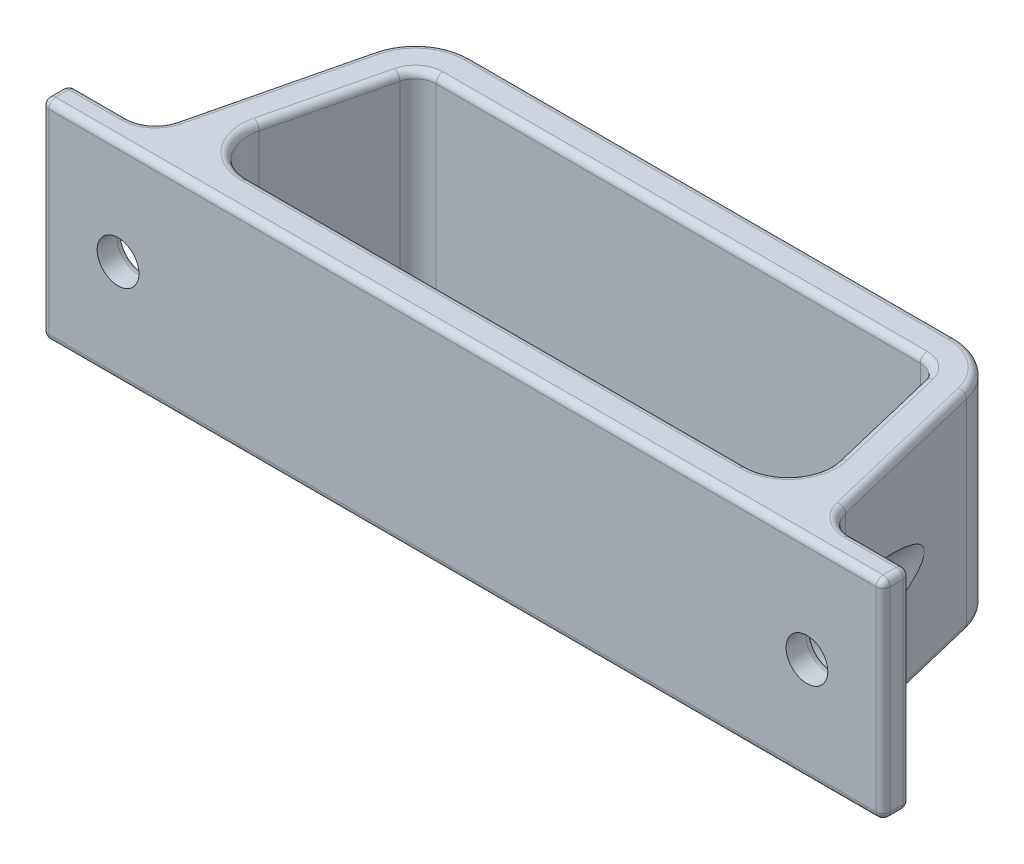
SolidWorks part; units mm, degrees
ref_plane "Front Plane" through (0, 0, 0) normal (0, 0, 1) x (1, 0, 0)
ref_plane "Top Plane" through (0, 0, 0) normal (0, 1, 0) x (1, 0, 0)
ref_plane "Right Plane" through (0, 0, 0) normal (1, 0, 0) x (0, 0, -1)
sketch "Sketch1" plane through (0, 0, 0) normal (0, 1, 0) x (1, 0, 0)
  line L15 (-28.2557, 3.4685) -> (-25.4887, 14.9381)
  line L16 (-30.1999, 1.9375) -> (-33.9268, 1.9375)
  line L17 (-34.4268, 1.4375) -> (-34.4268, 0.5)
  line L30 (-25.0241, 6.2036) -> (-23.0584, 14.3518)
  line L31 (25.8254, 2.8822) -> (23.0584, 14.3518) construction
  line L32 (-25.9357, 2.5) -> (25.9357, 2.5) construction
  line L33 (-25.8254, 2.8822) -> (-23.0584, 14.3518) construction
  line L35 (32.75, 1.4375) -> (32.75, 0.5) construction
  line L36 (30.1999, 1.9375) -> (32.25, 1.9375) construction
  line L37 (28.2557, 3.4685) -> (25.4887, 14.9381) construction
  line L38 (-21.6002, 18) -> (21.6002, 18) construction
  line L39 (-33.9268, 0) -> (32.25, 0) construction
  line L40 (-21.6002, 15.5) -> (21.6002, 15.5) construction
  line L41 (25.9357, 2.5) -> (25.9357, 2.5) construction
  line L42 (25.9357, 2.5) -> (25.9357, 2.5) construction
  line L48 (-25.9357, 2.5) -> (-25.9357, 2.5) construction
  line L49 (-25.9357, 2.5) -> (-25.9357, 2.5) construction
  line L50 (-4.205, 18) -> (-4.205, -5.5278) construction
  line L57 (16.6141, 6.2036) -> (14.6483, 14.3518)
  line L58 (26.0167, 1.4375) -> (26.0167, 0.5)
  line L59 (21.7898, 1.9375) -> (25.5167, 1.9375)
  line L60 (19.8456, 3.4685) -> (17.0786, 14.9381)
  line L61 (-33.9268, 0) -> (25.5167, 0)
  line L62 (13.6977, 2.5) -> (-22.1078, 2.5)
  line L63 (-21.6002, 15.5) -> (13.1902, 15.5)
  line L64 (13.1902, 18) -> (-21.6002, 18)
  arc A0 (-21.6002, 18) -> (-25.4887, 14.9381) centre (-21.6002, 14) ccw
  arc A1 (-30.1999, 1.9375) -> (-28.2557, 3.4685) centre (-30.1999, 3.9375) ccw
  arc A2 (-33.9268, 0) -> (-34.4268, 0.5) centre (-33.9268, 0.5) cw
  arc A3 (-34.4268, 1.4375) -> (-33.9268, 1.9375) centre (-33.9268, 1.4375) cw
  arc A13 (-25.9357, 2.5) -> (-25.9357, 2.5) centre (-25.9357, 2.5) cw
  arc A15 (-21.6002, 15.5) -> (-23.0584, 14.3518) centre (-21.6002, 14) ccw
  arc A17 (-22.1078, 2.5) -> (-25.0241, 6.2036) centre (-22.1078, 5.5) cw
  arc A18 (32.75, 1.4375) -> (32.25, 1.9375) centre (32.25, 1.4375) ccw construction
  arc A19 (32.25, 0) -> (32.75, 0.5) centre (32.25, 0.5) ccw construction
  arc A20 (30.1999, 1.9375) -> (28.2557, 3.4685) centre (30.1999, 3.9375) cw construction
  arc A21 (21.6002, 18) -> (25.4887, 14.9381) centre (21.6002, 14) cw construction
  arc A22 (21.6002, 15.5) -> (23.0584, 14.3518) centre (21.6002, 14) cw construction
  arc A23 (25.9357, 2.5) -> (25.8254, 2.8822) centre (30.1999, 3.9375) cw construction
  arc A24 (25.9357, 2.5) -> (25.9357, 2.5) centre (25.9357, 2.5) ccw construction
  arc A25 (25.9357, 2.5) -> (25.9357, 2.5) centre (25.9357, 2.5) ccw construction
  arc A30 (-25.9357, 2.5) -> (-25.8254, 2.8822) centre (-30.1999, 3.9375) ccw construction
  arc A31 (-25.9357, 2.5) -> (-25.9357, 2.5) centre (-25.9357, 2.5) cw construction
  arc A35 (13.6977, 2.5) -> (16.6141, 6.2036) centre (13.6977, 5.5) ccw
  arc A36 (13.1902, 15.5) -> (14.6483, 14.3518) centre (13.1902, 14) cw
  arc A37 (26.0167, 1.4375) -> (25.5167, 1.9375) centre (25.5167, 1.4375) ccw
  arc A38 (25.5167, 0) -> (26.0167, 0.5) centre (25.5167, 0.5) ccw
  arc A39 (21.7898, 1.9375) -> (19.8456, 3.4685) centre (21.7898, 3.9375) cw
  arc A40 (13.1902, 18) -> (17.0786, 14.9381) centre (13.1902, 14) cw
  point P16 (-34.4268, 0)
  point P66 (26.0167, 0)
  point P76 (-4.205, -2.7838)
  dimension "D4" = 4
  dimension "D5" = 2
  dimension "D6" = 0.5
  dimension "D1" = 2.5
extrude "Boss-Extrude3" add sketch "Sketch1" along normal blind 15 contours A40 L64 A0 L15 A1 L16 A3 L17 A2 L61 A38 L58 A37 L59 A39 L60 L63 A36 L57 A35 L62 A17 L30 A15
sketch "Sketch9" plane through (0, 0, 0) normal (0, 0, 1) x (1, 0, 0)
  line L0 (-4.205, 15) -> (-4.205, 0) construction
  line L1 (-33.9268, 15) -> (25.5167, 15) construction
  line L2 (-33.9268, 0) -> (25.5167, 0) construction
  line L3 (20.545, 7.5) -> (-28.955, 7.5)
  circle A0 centre (-28.955, 7.5) radius 1.5
  circle A1 centre (20.545, 7.5) radius 1.5
  point P9 (-4.205, 7.5)
extrude "Cut-Extrude1" cut sketch "Sketch9" against normal blind 15
sketch "Sketch10" plane through (0, 0, -18) normal (0, 0, -1) x (-1, 0, 0)
  line L0 (4.205, 15) -> (4.205, 0) construction
  line L1 (-13.1902, 15) -> (21.6002, 15) construction
  line L2 (-13.1902, 0) -> (21.6002, 0) construction
  line L3 (28.955, 7.5) -> (-20.545, 7.5)
  circle A0 centre (-20.545, 7.5) radius 2.5
  circle A1 centre (28.955, 7.5) radius 2.5
  point P9 (4.205, 7.5)
extrude "Cut-Extrude2" cut sketch "Sketch10" against normal up to surface (16.0625 mm away) up to face at (23.0746, 7.5, -1.9375)
fillet "Fillet1" radius 0.5 50 edges at (-22.5282, 0, -15.1785) (-24.0413, 0, -10.2777) (-24.4648, 0, -3.644) (-4.205, 0, -2.5) (16.0547, 0, -3.644) (15.6312, 0, -10.2777) (14.1182, 0, -15.1785) (-22.5282, 15, -15.1785) (-24.0413, 15, -10.2777) (-24.4648, 15, -3.644) (-4.205, 15, -2.5) (16.0547, 15, -3.644) (15.6312, 15, -10.2777) (14.1182, 15, -15.1785) (15.6648, 15, -17.1426) (18.4621, 15, -9.2033) (20.5525, 15, -2.3662) (23.6533, 15, -1.9375) (25.8703, 15, -1.7911) (26.0167, 15, -0.9687) (25.8703, 15, -0.1464) (-4.205, 15, 0) (-34.2803, 15, -0.1464) (-34.4268, 15, -0.9687) (-34.2803, 15, -1.7911) (-32.0633, 15, -1.9375) (-28.9626, 15, -2.3662) (-26.8722, 15, -9.2033) (-24.0749, 15, -17.1426) (15.6648, 0, -17.1426) (18.4621, 0, -9.2033) (20.5525, 0, -2.3662) (23.6533, 0, -1.9375) (25.8703, 0, -1.7911) (26.0167, 0, -0.9687) (25.8703, 0, -0.1464) (-4.205, 0, 0) (-34.2803, 0, -0.1464) (-34.4268, 0, -0.9687) (-34.2803, 0, -1.7911) (-32.0633, 0, -1.9375) (-28.9626, 0, -2.3662) (-26.8722, 0, -9.2033) (-24.0749, 0, -17.1426) (-27.455, 7.5, -1.9375) (19.045, 7.5, -1.9375) (-4.205, 0, -15.5) (-4.205, 15, -15.5) (-4.205, 15, -18) (-4.205, 0, -18)
